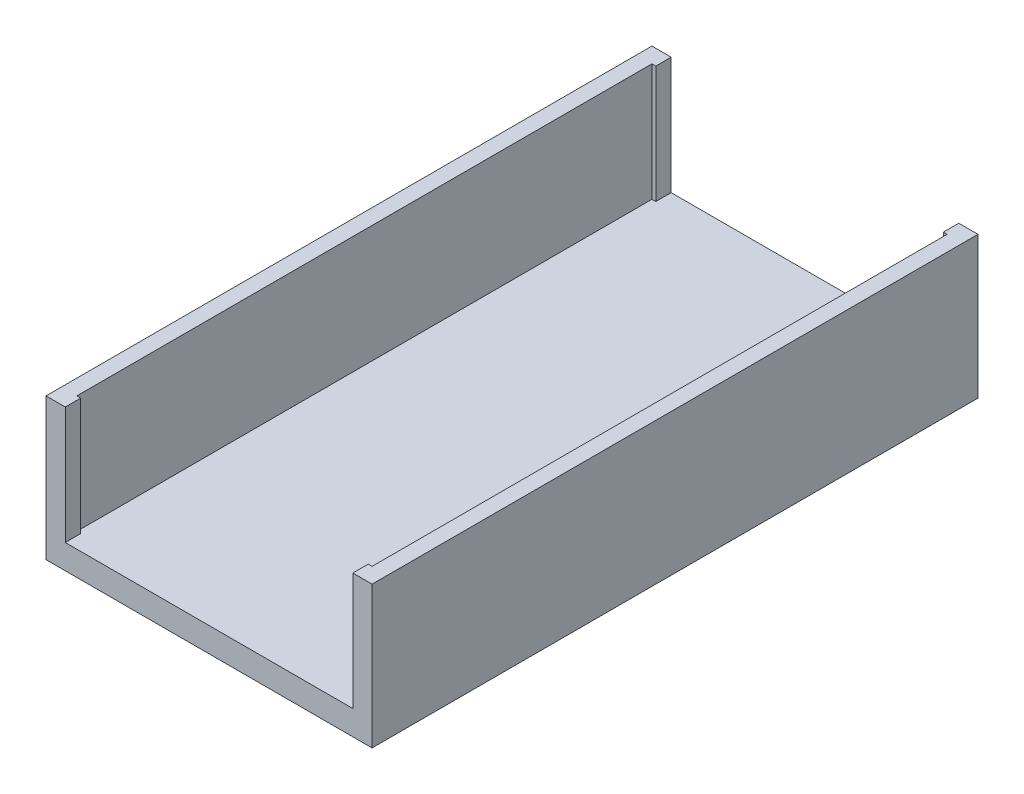
SolidWorks part; units mm, degrees
ref_plane "Front Plane" through (0, 0, 0) normal (0, 0, 1) x (1, 0, 0)
ref_plane "Top Plane" through (0, 0, 0) normal (0, 1, 0) x (1, 0, 0)
ref_plane "Right Plane" through (0, 0, 0) normal (1, 0, 0) x (0, 0, -1)
sketch "Sketch1" plane through (0, 0, 0) normal (0, 1, 0) x (1, 0, 0)
  line L1 (0, 0) -> (64.516, 0)
  line L2 (0, 0) -> (0, 119.888)
  line L3 (0, 119.888) -> (64.516, 119.888)
  line L4 (64.516, 0) -> (64.516, 119.888)
  line L5 (0, 0) -> (64.516, 119.888) construction
  line L6 (0, 119.888) -> (64.516, 0) construction
  point P4 (32.258, 59.944)
  dimension "D1" = 64.516
  dimension "D2" = 119.888
extrude "Boss-Extrude1" add sketch "Sketch1" along normal blind 28.067
sketch "Sketch2" plane through (0, 28.067, 0) normal (0, 1, 0) x (1, 0, 0)
  line L14 (3.048, 3.048) -> (61.468, 3.048)
  line L15 (61.468, 3.048) -> (61.468, 116.84)
  line L16 (3.048, 116.84) -> (3.048, 3.048)
  line L17 (61.468, 116.84) -> (3.048, 116.84)
  line L18 (3.048, 3.048) -> (61.468, 3.048)
  line L19 (61.468, 3.048) -> (61.468, 116.84)
  line L20 (3.048, 116.84) -> (3.048, 3.048)
  line L21 (61.468, 116.84) -> (3.048, 116.84)
  dimension "D1" = 3.048
extrude "Cut-Extrude1" cut sketch "Sketch2" against normal blind 23.2156
sketch "Sketch3" plane through (0, 28.067, 0) normal (0, 1, 0) x (1, 0, 0)
  line L0 (61.468, 116.84) -> (3.048, 116.84) construction
  line L1 (3.81, 116.84) -> (60.706, 116.84)
  line L2 (3.81, 116.84) -> (3.81, 119.888)
  line L3 (3.81, 119.888) -> (60.706, 119.888)
  line L4 (60.706, 116.84) -> (60.706, 119.888)
  line L5 (3.81, 116.84) -> (60.706, 119.888) construction
  line L6 (3.81, 119.888) -> (60.706, 116.84) construction
  line L7 (64.516, 119.888) -> (0, 119.888) construction
  line L8 (3.048, 3.048) -> (61.468, 3.048) construction
  line L9 (3.81, 3.048) -> (60.706, 3.048)
  line L10 (3.81, 3.048) -> (3.81, 0)
  line L11 (3.81, 0) -> (60.706, 0)
  line L12 (60.706, 3.048) -> (60.706, 0)
  line L13 (3.81, 3.048) -> (60.706, 0) construction
  line L14 (3.81, 0) -> (60.706, 3.048) construction
  line L15 (0, 0) -> (64.516, 0) construction
  line L16 (32.258, 118.364) -> (32.258, 1.524) construction
  line L17 (3.048, 59.944) -> (61.468, 59.944) construction
  line L18 (3.048, 116.84) -> (3.048, 3.048) construction
  line L19 (61.468, 3.048) -> (61.468, 116.84) construction
  point P4 (32.258, 118.364)
  point P13 (32.258, 1.524)
  point P26 (32.258, 59.944)
  dimension "D1" = 56.896
extrude "Cut-Extrude2" cut sketch "Sketch3" against normal blind 23.2156
